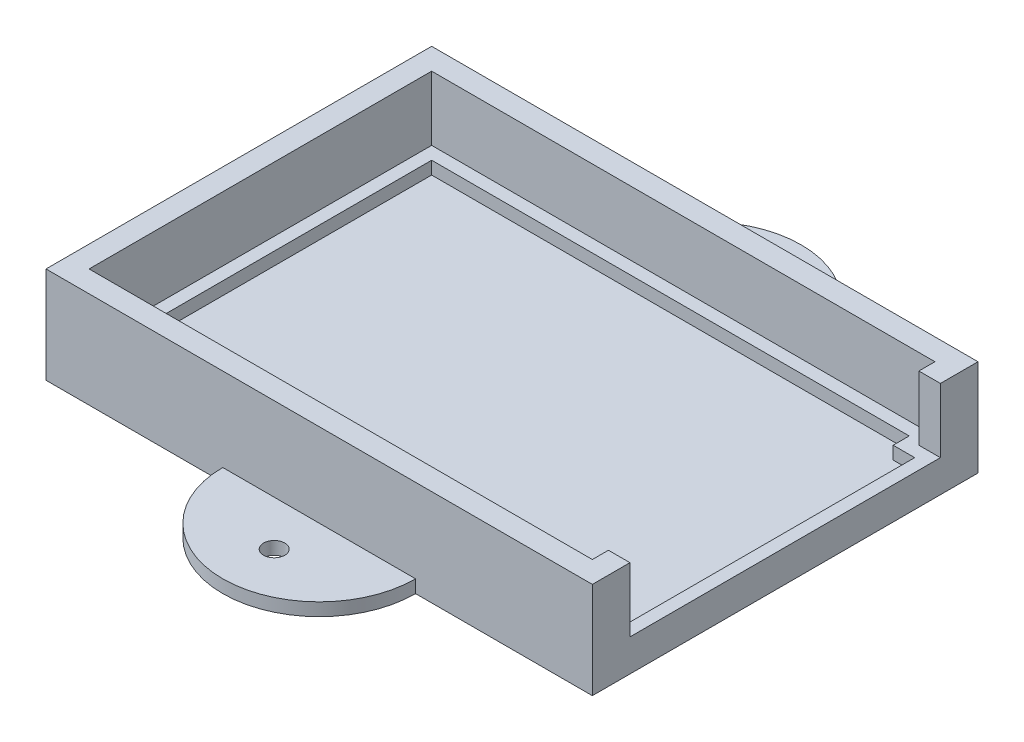
SolidWorks part; units mm, degrees
material "ABS"
ref_plane "Alzado" through (0, 0, 0) normal (0, 0, 1) x (1, 0, 0)
ref_plane "Planta" through (0, 0, 0) normal (0, 1, 0) x (1, 0, 0)
ref_plane "Vista lateral" through (0, 0, 0) normal (1, 0, 0) x (0, 0, -1)
sketch "Croquis2" plane through (0, 0, 0) normal (0, 1, 0) x (1, 0, 0)
  line L1 (42.5, -30) -> (-42.5, -30)
  line L2 (42.5, -30) -> (42.5, 30)
  line L3 (42.5, 30) -> (-42.5, 30)
  line L4 (-42.5, -30) -> (-42.5, 30)
  line L5 (42.5, -30) -> (-42.5, 30) construction
  line L6 (42.5, 30) -> (-42.5, -30) construction
  point P0 (0, 0)
  dimension "D1" = 85
  dimension "D2" = 60
extrude "Saliente-Extruir1" add sketch "Croquis2" along normal blind 15
shell "Vaciado1" thickness 3
sketch "Croquis3" plane through (0, 3, 0) normal (0, 1, 0) x (1, 0, 0)
  line L1 (-39.15, -26.65) -> (39.15, -26.65)
  line L2 (-39.15, -26.65) -> (-39.15, 26.65)
  line L3 (-39.15, 26.65) -> (39.15, 26.65)
  line L4 (39.15, -26.65) -> (39.15, 26.65)
  line L5 (-39.15, -26.65) -> (39.15, 26.65) construction
  line L6 (-39.15, 26.65) -> (39.15, -26.65) construction
  line L7 (-39.5, 27) -> (39.5, 27)
  line L8 (-39.5, 27) -> (-39.5, -27)
  line L9 (-39.5, -27) -> (39.5, -27)
  line L10 (39.5, 27) -> (39.5, -27)
  point P0 (0, 0)
  dimension "D1" = 53.3
  dimension "D2" = 78.3
extrude "Saliente-Extruir2" add sketch "Croquis3" along normal up to vertex (12 mm away)
sketch "Croquis6" plane through (0, 15, 0) normal (0, 1, 0) x (1, 0, 0)
  line L0 (39.15, -26.65) -> (39.15, 26.65) construction
  line L1 (39.15, 24.15) -> (42.5, 24.15)
  line L2 (39.15, 24.15) -> (39.15, -24.15)
  line L3 (39.15, -24.15) -> (42.5, -24.15)
  line L4 (42.5, 24.15) -> (42.5, -24.15)
  line L5 (42.5, -30) -> (42.5, 30) construction
  line L6 (-39.15, -26.65) -> (39.15, -26.65) construction
  line L7 (39.15, 26.65) -> (-39.15, 26.65) construction
  dimension "D1" = 2.5
  dimension "D2" = 2.5
extrude "Cortar-Extruir2" cut sketch "Croquis6" against normal up to surface (12 mm away) up to face at (0, 3, 0)
sketch "Croquis7" plane through (0, 3, 0) normal (0, 1, 0) x (1, 0, 0)
  line L0 (37.15, -24.65) -> (37.15, -22.15)
  line L1 (37.15, -22.15) -> (40.5, -22.15)
  line L2 (40.5, -22.15) -> (40.5, 22.15)
  line L3 (40.5, 22.15) -> (37.15, 22.15)
  line L4 (37.15, 22.15) -> (37.15, 24.65)
  line L5 (37.15, 24.65) -> (-37.15, 24.65)
  line L6 (-37.15, 24.65) -> (-37.15, -24.65)
  line L7 (-37.15, -24.65) -> (37.15, -24.65)
  line L8 (39.15, -26.65) -> (39.15, -24.15)
  line L9 (39.15, -24.15) -> (42.5, -24.15)
  line L10 (42.5, -24.15) -> (42.5, 24.15)
  line L11 (42.5, 24.15) -> (39.15, 24.15)
  line L12 (39.15, 24.15) -> (39.15, 26.65)
  line L13 (39.15, 26.65) -> (-39.15, 26.65)
  line L14 (-39.15, 26.65) -> (-39.15, -26.65)
  line L15 (-39.15, -26.65) -> (39.15, -26.65)
  line L16 (39.15, -26.65) -> (39.15, -24.15)
  line L17 (39.15, -24.15) -> (42.5, -24.15)
  line L18 (42.5, -24.15) -> (42.5, 24.15)
  line L19 (42.5, 24.15) -> (39.15, 24.15)
  line L20 (39.15, 24.15) -> (39.15, 26.65)
  line L21 (39.15, 26.65) -> (-39.15, 26.65)
  line L22 (-39.15, 26.65) -> (-39.15, -26.65)
  line L23 (-39.15, -26.65) -> (39.15, -26.65)
  dimension "D1" = 0
  dimension "D2" = 2
extrude "Saliente-Extruir4" add sketch "Croquis7" along normal blind 2
sketch "Croquis8" plane through (0, 0, 0) normal (0, -1, 0) x (1, 0, 0)
  line L0 (0, -30) -> (0, 30) construction
  line L1 (42.5, -30) -> (-42.5, -30) construction
  line L2 (-15, -30) -> (-15, 30)
  line L3 (15, -30) -> (15, 30)
  line L4 (-42.5, 30) -> (42.5, 30) construction
  arc A0 (-15, -30) -> (15, -30) centre (0, -30) ccw
  arc A1 (15, 30) -> (-15, 30) centre (0, 30) ccw
  point P5 (0, 0)
  point P10 (0, 0)
  dimension "D1" = 15
extrude "Saliente-Extruir5" add sketch "Croquis8" against normal blind 2
sketch "Croquis9" plane through (0, 2, 0) normal (0, 1, 0) x (1, 0, 0)
  line L0 (-15, 30) -> (15, 30) construction
  line L1 (-42.5, -30) -> (42.5, -30) construction
  circle A0 centre (0, 37) radius 1.65
  circle A1 centre (0, -37) radius 1.65
  point P9 (0, 0)
  dimension "D1" = 3.3
  dimension "D3" = 3.3
  dimension "D2" = 7
  dimension "D4" = 7
extrude "Cortar-Extruir3" cut sketch "Croquis9" against normal blind 21
